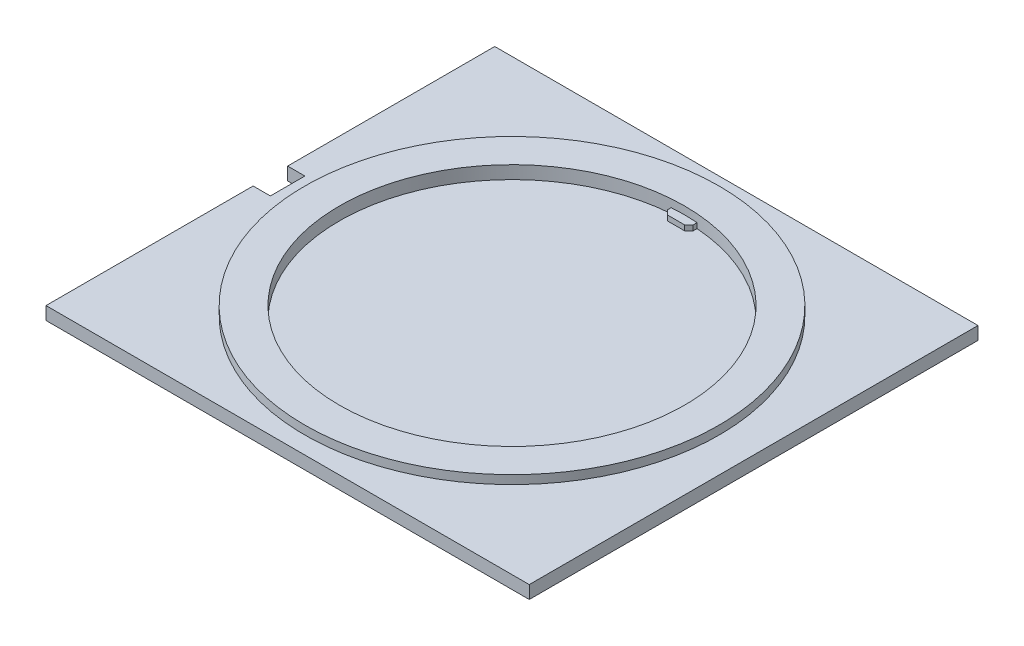
SolidWorks part; units mm, degrees
ref_plane "Front Plane" through (0, 0, 0) normal (0, 0, 1) x (1, 0, 0)
ref_plane "Top Plane" through (0, 0, 0) normal (0, 1, 0) x (1, 0, 0)
ref_plane "Right Plane" through (0, 0, 0) normal (1, 0, 0) x (0, 0, -1)
sketch "Sketch1" plane through (0, 0, 0) normal (0, 1, 0) x (1, 0, 0)
  circle A0 centre (0, 0) radius 20
  circle A1 centre (0, 0) radius 24
  dimension "D1" = 48
  dimension "D2" = 40
extrude "Boss-Extrude1" add sketch "Sketch1" along normal blind 2.5
sketch "Sketch2" plane through (0, 0, 0) normal (0, -1, 0) x (1, 0, 0)
  circle A0 centre (0, 0) radius 24 construction
  circle A1 centre (0, 0) radius 24
extrude "Boss-Extrude2" add sketch "Sketch2" against normal blind 1
sketch "Sketch3" plane through (0, 0, 0) normal (0, -1, 0) x (1, 0, 0)
  line L1 (-28, -26) -> (28, -26)
  line L2 (-28, -26) -> (-28, 26)
  line L3 (-28, 26) -> (28, 26)
  line L4 (28, -26) -> (28, 26)
  line L5 (-28, -26) -> (28, 26) construction
  line L6 (-28, 26) -> (28, -26) construction
  circle A0 centre (0, 0) radius 24 construction
  circle A1 centre (0, 0) radius 24
  dimension "D1" = 4
  dimension "D2" = 2
extrude "Boss-Extrude3" add sketch "Sketch3" against normal up to surface (1.5 mm away)
sketch "Sketch4" plane through (0, 1, 0) normal (0, 1, 0) x (1, 0, 0)
  line L0 (0, 0) -> (0, 48.604) construction
  line L1 (1.5, 25.6475) -> (1.5, 19)
  line L6 (1.5, 25.6475) -> (-1.5, 25.6475)
  line L7 (1.5, 19) -> (-1.5, 19)
  line L8 (-1.5, 25.6475) -> (-1.5, 19)
  line L9 (1.5, 25.6475) -> (-1.5, 19) construction
  line L10 (1.5, 19) -> (-1.5, 25.6475) construction
  circle A0 centre (0, 0) radius 20 construction
  circle A1 centre (0, 0) radius 20
  point P0 (0.1128, 48.6034)
  point P6 (0, 22.3238)
  circle M12 centre (0, 0) radius 20
  dimension "D1" = 3
  dimension "D2" = 1
extrude "Boss-Extrude4" add sketch "Sketch4" along normal blind 0.6 contours L8 L7 L1 M12
chamfer "Chamfer1" distance 0.5 angle 45 2 edges at (1.5, 1.3, -19) (-1.5, 1.3, -19)
sketch "Sketch5" plane through (0, 0, 0) normal (0, -1, 0) x (1, 0, 0)
  line L0 (0, 0) -> (-77.1173, 0) construction
  line L1 (-28, 26) -> (-28, -26) construction
  line L2 (-44.1883, -2) -> (-26, -2)
  line L3 (-44.1883, -2) -> (-44.1883, 2)
  line L4 (-44.1883, 2) -> (-26, 2)
  line L5 (-26, -2) -> (-26, 2)
  line L6 (-44.1883, -2) -> (-26, 2) construction
  line L7 (-44.1883, 2) -> (-26, -2) construction
  point P3 (-35.0941, 0)
  dimension "D1" = 2
  dimension "D2" = 4
extrude "Cut-Extrude1" cut sketch "Sketch5" against normal through all
